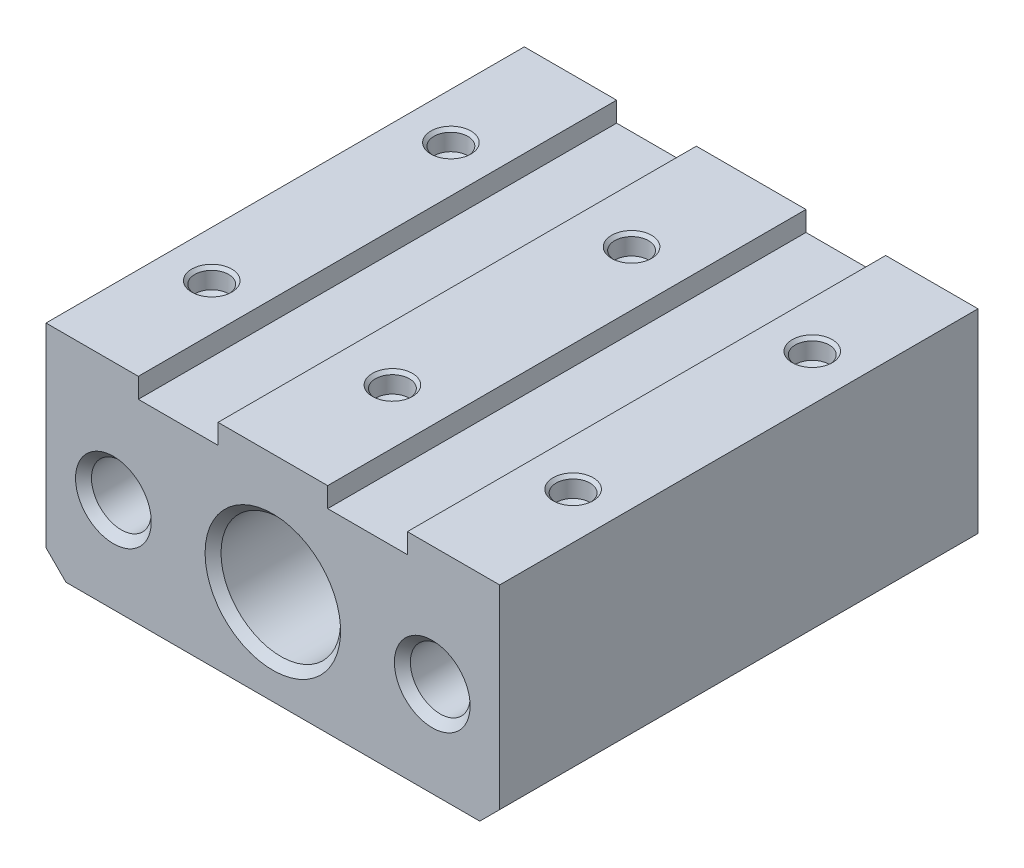
SolidWorks part; units mm, degrees
ref_plane "前视基准面" through (0, 0, 0) normal (0, 0, 1) x (1, 0, 0)
ref_plane "上视基准面" through (0, 0, 0) normal (0, 1, 0) x (1, 0, 0)
ref_plane "右视基准面" through (0, 0, 0) normal (1, 0, 0) x (0, 0, -1)
other "Configuration Table"
sketch "草图1" plane through (0, 0, 0) normal (0, 1, 0) x (1, 0, 0)
  line L1 (-60.2041, 34.9936) -> (60.2041, 34.9936)
  line L2 (-60.2041, 34.9936) -> (-60.2041, -34.9936)
  line L3 (-60.2041, -34.9936) -> (60.2041, -34.9936)
  line L4 (60.2041, 34.9936) -> (60.2041, -34.9936)
  line L5 (-60.2041, 34.9936) -> (60.2041, -34.9936) construction
  line L6 (-60.2041, -34.9936) -> (60.2041, 34.9936) construction
  point P0 (0, 0)
extrude "凸台-拉伸1" add sketch "草图1" along normal blind 30
sketch "草图2" plane through (0, 0, 34.9936) normal (0, 0, 1) x (1, 0, 0)
  line L0 (-56.909, -14.965) -> (-56.909, 33.7808)
  line L1 (-56.909, 0) -> (-56.909, -20) construction
  line L2 (-56.909, 53.8253) -> (-56.909, 0) construction
  line L3 (-56.909, 33.7808) -> (-66.3045, 33.7808)
  line L4 (-66.3045, 33.7808) -> (-66.3045, -14.965)
  line L5 (-66.3045, -14.965) -> (-56.909, -14.965)
  line L6 (56.909, -11.8466) -> (56.909, 33.7808)
  line L7 (56.909, -20) -> (56.909, 0) construction
  line L8 (56.909, 53.8253) -> (56.909, 0) construction
  line L9 (56.909, 33.7808) -> (63.6845, 33.7808)
  line L10 (63.6845, 33.7808) -> (62.9134, -11.8466)
  line L11 (62.9134, -23.4086) -> (62.9134, -5.5914) construction
  line L12 (62.9134, -11.8466) -> (56.909, -11.8466)
extrude "切除-拉伸1" cut sketch "草图2" against normal through all both and the other way through all
sketch "草图3" plane through (0, 0, 34.9936) normal (0, 0, 1) x (1, 0, 0)
  line L0 (56.909, 0) -> (56.909, 30) construction
  line L1 (-56.909, 30) -> (56.909, 30)
  line L2 (-56.909, 30) -> (-56.909, 60)
  line L3 (-56.909, 60) -> (56.909, 60)
  line L4 (56.909, 30) -> (56.909, 60)
  line L5 (-56.909, 0) -> (56.909, 0) construction
  dimension "D1" = 60
extrude "凸台-拉伸2" add sketch "草图3" against normal up to surface (69.9873 mm away) up to face at (0, 15, -34.9936)
sketch "草图4" plane through (0, 0, 34.9936) normal (0, 0, 1) x (1, 0, 0)
  line L0 (-56.909, 60) -> (56.909, 60)
  line L2 (56.909, 60) -> (56.909, 63.8253)
  line L3 (56.909, 63.8253) -> (-56.909, 63.8253)
  line L4 (-56.909, -175) -> (-56.909, 194.7626) construction
  line L5 (-56.909, 63.8253) -> (-56.909, 60)
  circle A0 centre (-40, 33.8253) radius 7.5 construction
  dimension "D1" = 30
extrude "凸台-拉伸3" add sketch "草图4" against normal up to surface (69.9873 mm away) up to face at (0, 30, -34.9936)
sketch "草图5" plane through (56.909, 0, 0) normal (1, 0, 0) x (0, 0, -1)
  line L0 (-287.0151, 0) -> (44.2349, 0) construction
  line L1 (-34.9936, 63.8253) -> (85.0064, 63.8253)
  line L2 (-34.9936, 63.8253) -> (-34.9936, 0)
  line L3 (-34.9936, 0) -> (85.0064, 0)
  line L4 (85.0064, 63.8253) -> (85.0064, 0)
  dimension "D1" = 120
extrude "凸台-拉伸4" add sketch "草图5" against normal up to surface (113.8179 mm away) up to face at (-56.909, 31.9127, 0)
sketch "草图6" plane through (0, 0, 34.9936) normal (0, 0, 1) x (1, 0, 0)
  circle A0 centre (0, 33.8253) radius 15
  circle A1 centre (-40, 33.8253) radius 7.5
  circle A2 centre (40, 33.8253) radius 7.5
extrude "切除-拉伸2" cut sketch "草图6" against normal through all both and the other way through all
sketch "草图7" plane through (0, 0, 34.9936) normal (0, 0, 1) x (1, 0, 0)
  line L0 (-56.909, 10) -> (56.909, 10)
  line L1 (-56.909, 63.8253) -> (-56.909, 0) construction
  line L2 (56.909, 0) -> (56.909, 63.8253) construction
  line L3 (-56.909, 0) -> (56.909, 0) construction
  line L4 (-56.909, 10) -> (-56.909, -1.2345)
  line L5 (-56.909, 0) -> (-56.909, -20) construction
  line L6 (-56.909, -1.2345) -> (56.909, -1.2345)
  line L7 (56.909, -20) -> (56.909, 0) construction
  line L8 (56.909, -1.2345) -> (56.909, 10)
  dimension "D1" = 10
extrude "切除-拉伸3" cut sketch "草图7" against normal through all both and the other way through all
sketch "草图8" plane through (0, 0, 34.9936) normal (0, 0, 1) x (1, 0, 0)
  line L0 (56.909, 63.8253) -> (-56.909, 63.8253) construction
  line L1 (-33.75, 63.8253) -> (-13.75, 63.8253)
  line L2 (-33.75, 63.8253) -> (-33.75, 58.8253)
  line L3 (-33.75, 58.8253) -> (-13.75, 58.8253)
  line L4 (-13.75, 63.8253) -> (-13.75, 58.8253)
  line L5 (-18.75, 0) -> (-18.75, 53.8253) construction
  line L6 (13.75, 63.8253) -> (33.75, 63.8253)
  line L7 (13.75, 63.8253) -> (13.75, 58.8253)
  line L8 (13.75, 58.8253) -> (33.75, 58.8253)
  line L9 (33.75, 63.8253) -> (33.75, 58.8253)
  line L10 (-28.75, 53.8253) -> (-28.75, 0) construction
  line L11 (18.75, 53.8253) -> (18.75, 0) construction
  line L12 (28.75, 0) -> (28.75, 53.8253) construction
  dimension "D1" = 5
  dimension "D2" = 5
  dimension "D3" = 5
  dimension "D4" = 5
  dimension "D5" = 5
  dimension "D6" = 5
extrude "切除-拉伸4" cut sketch "草图8" against normal through all both and the other way through all
chamfer "倒角1" distance 5 angle 45 2 edges at (56.909, 10, -25.0064) (-56.909, 10, -25.0064)
chamfer "倒角2" distance 2 angle 45 6 edges at (32.5, 33.8253, 34.9936) (47.5, 33.8253, -85.0064) (-15, 33.8253, 34.9936) (15, 33.8253, -85.0064) (-47.5, 33.8253, 34.9936) (-32.5, 33.8253, -85.0064)
sketch "草图9" plane through (0, 63.8253, 0) normal (0, 1, 0) x (1, 0, 0)
  line L0 (-45.3295, 85.0064) -> (-45.3295, -34.9936) construction
  line L1 (-56.909, 85.0064) -> (-33.75, 85.0064) construction
  line L2 (-33.75, -34.9936) -> (-56.909, -34.9936) construction
  line L3 (0, 85.0064) -> (0, -34.9936) construction
  line L4 (-13.75, 85.0064) -> (13.75, 85.0064) construction
  line L5 (13.75, -34.9936) -> (-13.75, -34.9936) construction
  line L6 (45.3295, 85.0064) -> (45.3295, -34.9936) construction
  line L7 (33.75, 85.0064) -> (56.909, 85.0064) construction
  line L8 (56.909, -34.9936) -> (33.75, -34.9936) construction
  point P18 (-45.3295, 55.0064)
  point P19 (-45.3295, -4.9936)
  point P20 (0, 55.0064)
  point P21 (0, -4.9936)
  point P22 (45.3295, -4.9936)
  point P23 (45.3295, 55.0064)
  dimension "D1" = 30
  dimension "D2" = 30
  dimension "D3" = 30
  dimension "D4" = 30
  dimension "D5" = 30
  dimension "D6" = 30
sketch "草图10" plane through (0, 63.8253, 0) normal (0, 1, 0) x (1, 0, 0)
  point P0 (-45.3295, 55.0064)
  point P3 (-45.3295, -4.9936)
  point P6 (0, -4.9936)
  point P9 (45.3295, -4.9936)
  point P12 (45.3295, 55.0064)
  point P15 (0, 55.0064)
hole_wizard "M10 螺纹孔1" positions "草图10" profile "草图11" tap size "M10" standard "GB"
sketch "草图11" plane through (-45.3295, 63.8253, -55.0064) normal (1, 0, 0) x (0, 0, 1)
  line L0 (0, 0) -> (0, 7.5537)
  line L1 (0, 7.5537) -> (4.25, 5)
  line L2 (4.25, 5) -> (4.25, 0.775)
  line L3 (4.25, 0.775) -> (5.025, 0)
  line L5 (5.025, 0) -> (0, 0)
  line L6 (-4.25, 0.775) -> (-5.025, 0) construction
  line L10 (0, 7.5537) -> (-4.25, 5) construction
  line L11 (0, -6.35) -> (0, 107.95) construction
  dimension "螺纹孔钻头直径" = 8.5
  dimension "螺纹孔钻头深度" = 5
  dimension "近端锥形沉头孔直径" = 10.05
  dimension "近端锥形沉头孔角度" = 90
  dimension "导头角度" = 118
cosmetic thread "孔螺蚊线1" parameters "D1"=5, "D2"=10
cosmetic thread "孔螺蚊线2" parameters "D1"=5, "D2"=10
cosmetic thread "孔螺蚊线3" parameters "D1"=5, "D2"=10
cosmetic thread "孔螺蚊线4" parameters "D1"=5, "D2"=10
cosmetic thread "孔螺蚊线5" parameters "D1"=5, "D2"=10
cosmetic thread "孔螺蚊线6" parameters "D1"=5, "D2"=10
